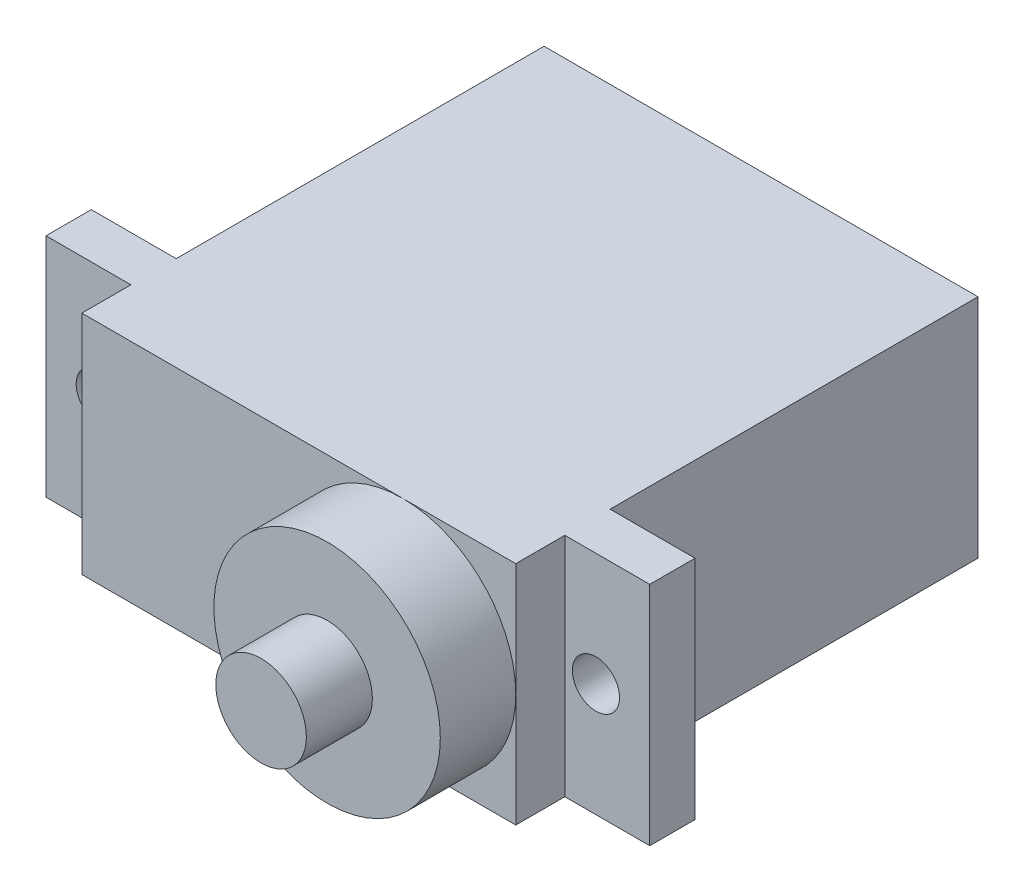
SolidWorks part; units mm, degrees
ref_plane "Front Plane" through (0, 0, 0) normal (0, 0, 1) x (1, 0, 0)
ref_plane "Top Plane" through (0, 0, 0) normal (0, 1, 0) x (1, 0, 0)
ref_plane "Right Plane" through (0, 0, 0) normal (1, 0, 0) x (0, 0, -1)
sketch "Sketch1" plane through (0, 0, 0) normal (0, 0, 1) x (1, 0, 0)
  line L1 (0, 0) -> (23, 0)
  line L2 (0, 0) -> (0, 12)
  line L3 (0, 12) -> (23, 12)
  line L4 (23, 0) -> (23, 12)
  dimension "D1" = 23
  dimension "D2" = 12
extrude "Boss-Extrude1" add sketch "Sketch1" along normal blind 32
sketch "Sketch2" plane through (0, 0, 32) normal (0, 0, 1) x (1, 0, 0)
  line L0 (23, 0) -> (23, 12) construction
  line L1 (0, 0) -> (23, 0) construction
  line L2 (23, 12) -> (0, 12) construction
  line L7 (0, 12) -> (0, 0)
  line L8 (0, 0) -> (23, 0)
  line L9 (23, 0) -> (23, 12)
  line L10 (23, 12) -> (0, 12)
  line L11 (0, 12) -> (0, 0)
  line L12 (0, 0) -> (23, 0)
  line L13 (23, 0) -> (23, 12)
  line L14 (23, 12) -> (0, 12)
  circle A0 centre (17, 6) radius 6
  line M5 (0, 12) -> (0, 0)
  line M6 (0, 0) -> (23, 0)
  line M7 (23, 0) -> (23, 12)
  line M8 (23, 12) -> (0, 12)
  dimension "D1" = 0
extrude "Cut-Extrude1" cut sketch "Sketch2" against normal blind 7.5 contours A0 L14 M5 M6 | A0 L13 M8 | A0 L12 M7
sketch "Sketch3" plane through (0, 0, 32) normal (0, 0, 1) x (1, 0, 0)
  circle A0 centre (17, 6) radius 2.4
  circle A2 centre (17, 6) radius 6
  circle A3 centre (17, 6) radius 6
  dimension "D1" = 4.8
  dimension "D2" = 0
extrude "Cut-Extrude2" cut sketch "Sketch3" against normal blind 3.5
ref_plane "Plane1" through (0, 0, 19.5) normal (0, 0, 1) x (1, 0, 0)
sketch "Sketch4" plane through (0, 0, 19.5) normal (0, 0, 1) x (1, 0, 0)
  line L0 (17, 12) -> (0, 12) construction
  line L1 (-4.5, 0) -> (27.5, 0)
  line L2 (-4.5, 0) -> (-4.5, 12)
  line L3 (-4.5, 12) -> (27.5, 12)
  line L4 (27.5, 0) -> (27.5, 12)
  line L5 (0, 0) -> (17, 0) construction
  line L6 (0, 12) -> (0, 0) construction
  circle A0 centre (24.65, 6) radius 1.25
  circle A1 centre (-1.65, 6) radius 1.25
  point P18 (0, 6)
  dimension "D3" = 2.5
  dimension "D1" = 4.5
  dimension "D2" = 32
  dimension "D4" = 2.85
  dimension "D5" = 2.85
extrude "Boss-Extrude2" add sketch "Sketch4" along normal blind 2.4
